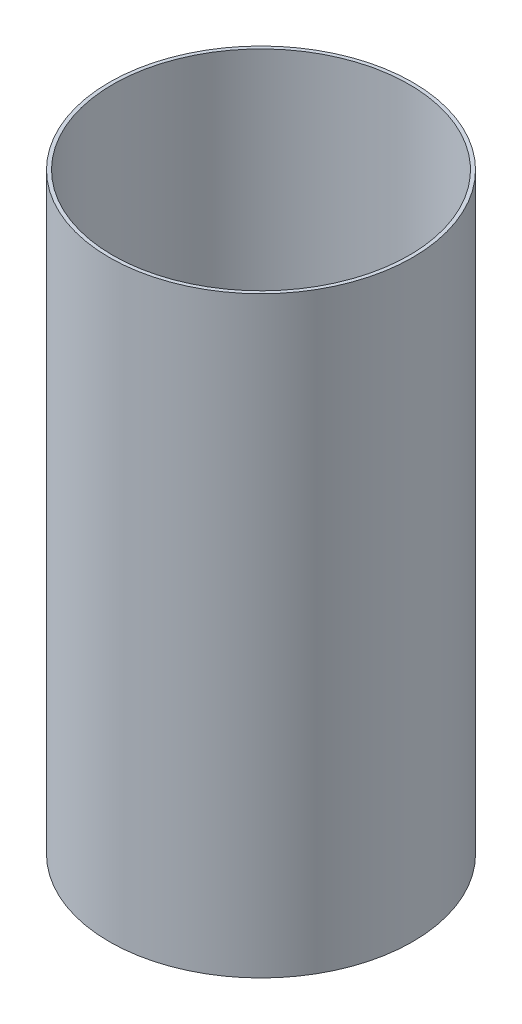
SolidWorks part; units mm, degrees
ref_plane "Front Plane" through (0, 0, 0) normal (0, 0, 1) x (1, 0, 0)
ref_plane "Top Plane" through (0, 0, 0) normal (0, 1, 0) x (1, 0, 0)
ref_plane "Right Plane" through (0, 0, 0) normal (1, 0, 0) x (0, 0, -1)
sketch "Sketch1" plane through (0, 0, 0) normal (0, 1, 0) x (1, 0, 0)
  circle A0 centre (0, 0) radius 128
  circle A1 centre (0, 0) radius 125
  dimension "D1" = 256
  dimension "D2" = 3
extrude "Boss-Extrude1" add sketch "Sketch1" along normal blind 500
